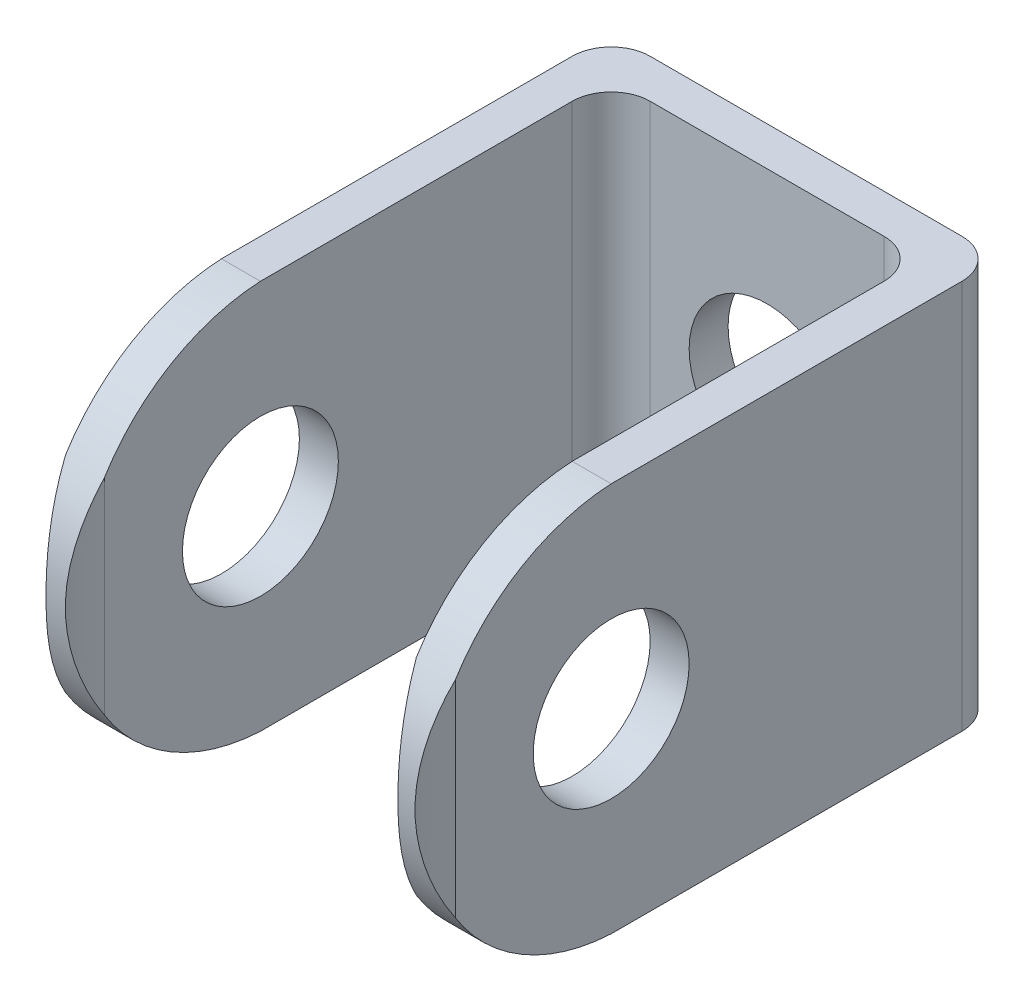
SolidWorks part; units mm, degrees
ref_plane "Спереди" through (0, 0, 0) normal (0, 0, 1) x (1, 0, 0)
ref_plane "Сверху" through (0, 0, 0) normal (0, 1, 0) x (1, 0, 0)
ref_plane "Справа" through (0, 0, 0) normal (1, 0, 0) x (0, 0, -1)
sketch "Эскиз1" plane through (0, 0, 0) normal (0, 1, 0) x (1, 0, 0)
  line L0 (0, 1) -> (0, 14)
  line L2 (1, 1) -> (1, 13)
  line L3 (1, 15) -> (9, 15)
  line L4 (2, 14) -> (8, 14)
  line L5 (10, 14) -> (10, 1)
  line L7 (9, 1) -> (9, 13)
  arc A0 (1, 13) -> (2, 14) centre (2, 13) cw
  arc A1 (1, 15) -> (0, 14) centre (1, 14) ccw
  arc A2 (9, 15) -> (10, 14) centre (9, 14) cw
  arc A3 (8, 14) -> (9, 13) centre (8, 13) cw
  spline S0 degree 2 poles (0, 1) (0.5, -1) (1, 1) knots 0 0 0 1 1 1
  spline S1 degree 3 poles (9, 1) (9.1667, 0.5) (9.5, -0.5) (9.8333, 0.5) (10, 1) knots 0 0 0 0 0.5 1 1 1 1
extrude "Бобышка-Вытянуть1" add sketch "Эскиз1" along normal blind 10
sketch "Эскиз3" plane through (10, 0, 0) normal (1, 0, 0) x (0, 0, -1)
  circle A0 centre (5, 5) radius 2
extrude "Вырез-Вытянуть3" cut sketch "Эскиз3" against normal blind 10 contours A0
sketch "Эскиз14" plane through (0, 0, 0) normal (1, 0, 0) x (0, 0, -1)
  line L0 (1, 10) -> (14, 10) construction
  line L1 (1, 0) -> (14, 0) construction
  line L2 (5, 10) -> (0, 10)
  line L3 (0, 10) -> (0, 0)
  line L4 (0, 0) -> (5, 0)
  arc A0 (5, 10) -> (5, 0) centre (5.2527, 5) ccw
  point P0 (5, 10)
  point P1 (5, 0)
extrude "Вырез-Вытянуть19" cut sketch "Эскиз14" along normal blind 10
sketch "Эскиз15" plane through (0, 0, -15) normal (0, 0, -1) x (-1, 0, 0)
  circle A0 centre (-5, 5) radius 2
extrude "Вырез-Вытянуть20" cut sketch "Эскиз15" against normal blind 10
